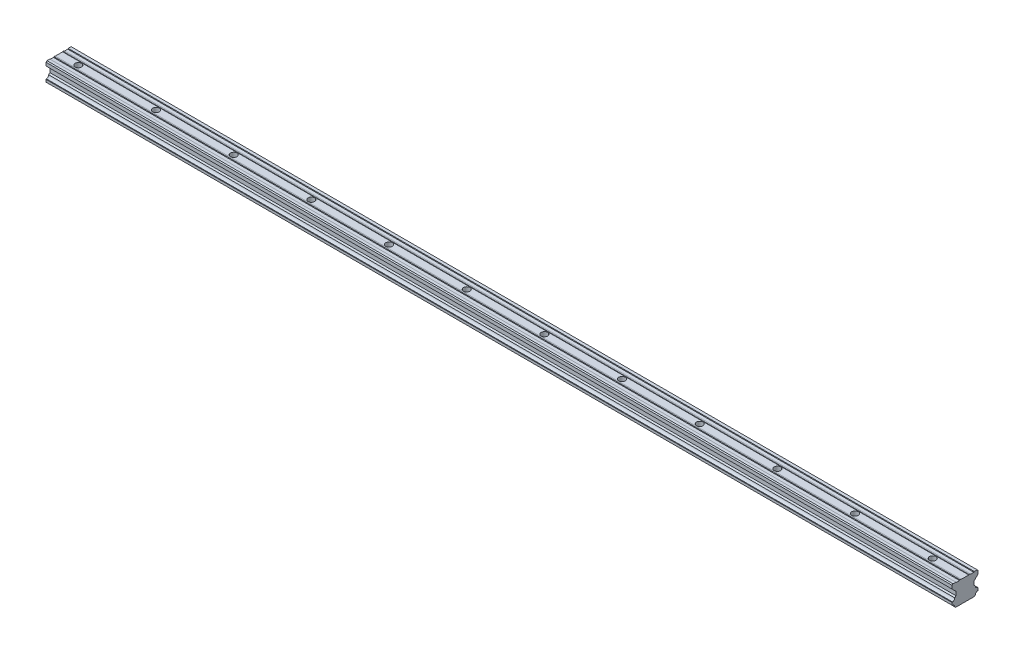
SolidWorks part; units mm, degrees
material "ASTM A36 Steel"
ref_plane "Front Plane" through (0, 0, 0) normal (0, 0, 1) x (1, 0, 0)
ref_plane "Top Plane" through (0, 0, 0) normal (0, 1, 0) x (1, 0, 0)
ref_plane "Right Plane" through (0, 0, 0) normal (1, 0, 0) x (0, 0, -1)
sketch "Sketch1" plane through (0, 0, 0) normal (1, 0, 0) x (0, 0, -1)
  line L0 (-7.9658, -7.694) -> (-7.2663, -8.3935)
  line L1 (-7.2663, -8.3935) -> (7.2663, -8.3935)
  line L2 (7.2663, -8.3935) -> (7.9658, -7.694)
  line L3 (9.7474, -5.9133) -> (10, -5.6608)
  line L4 (10, -5.6608) -> (10, -3.7884)
  line L5 (10, -3.7884) -> (9.7474, -3.5358)
  line L6 (7.9658, -1.7232) -> (7.0051, -0.7626)
  line L7 (7.0051, -0.7626) -> (7.0051, 2.1662)
  line L8 (7.0051, 2.1662) -> (10, 5.1611)
  line L9 (10, 5.1611) -> (10, 7.7124)
  line L10 (10, 7.7124) -> (9.4085, 8.3935)
  line L11 (9.4085, 8.3935) -> (7.133, 8.3935)
  line L12 (7.133, 8.3935) -> (6.7895, 8.05)
  line L13 (6.7895, 8.05) -> (4.2711, 8.05)
  line L14 (4.2711, 8.05) -> (3.9277, 8.3935)
  line L15 (3.9277, 8.3935) -> (3.0613, 8.3935)
  line L16 (3.0613, 8.3935) -> (2.872, 8.2042)
  line L17 (2.872, 8.2042) -> (-2.872, 8.2042)
  line L18 (-2.872, 8.2042) -> (-3.0613, 8.3935)
  line L19 (-3.0613, 8.3935) -> (-3.9277, 8.3935)
  line L20 (-3.9277, 8.3935) -> (-4.2712, 8.05)
  line L21 (-4.2712, 8.05) -> (-6.7895, 8.05)
  line L22 (-6.7895, 8.05) -> (-7.133, 8.3935)
  line L23 (-7.133, 8.3935) -> (-9.3077, 8.3935)
  line L24 (-9.3077, 8.3935) -> (-10, 7.7012)
  line L25 (-10, 7.7012) -> (-10, 5.1611)
  line L26 (-10, 5.1611) -> (-7.0051, 2.1662)
  line L27 (-7.0051, 2.1662) -> (-7.0051, -0.7626)
  line L28 (-7.0051, -0.7626) -> (-7.9658, -1.7232)
  line L29 (-9.7474, -5.9133) -> (-10, -5.6608)
  line L30 (-10, -5.6608) -> (-10, -3.7884)
  line L31 (-10, -3.7884) -> (-9.7474, -3.5358)
  arc A0 (-7.9658, -7.694) -> (-9.7474, -5.9133) centre (-9.7035, -7.6511) ccw
  arc A1 (-9.7474, -3.5358) -> (-7.9658, -1.7232) centre (-9.7025, -1.7981) ccw
  arc A2 (7.9658, -1.7232) -> (9.7474, -3.5358) centre (9.7025, -1.7981) ccw
  arc A3 (9.7474, -5.9133) -> (7.9658, -7.694) centre (9.7035, -7.6511) ccw
extrude "Boss-Extrude1" add sketch "Sketch1" along normal blind 700
sketch "Croquis1" plane through (0, -8.3935, 0) normal (0, -1, 0) x (1, 0, 0)
  line L0 (0, 0) -> (15, 0) construction
  circle A0 centre (15, 0) radius 2.5
  dimension "D1" = 5
  dimension "D2" = 15
extrude "Cortar-Extruir1" cut sketch "Croquis1" against normal blind 20
pattern_linear "MatrizL1" count 12 spacing 60 along (1, 0, 0) of "Cortar-Extruir1"
